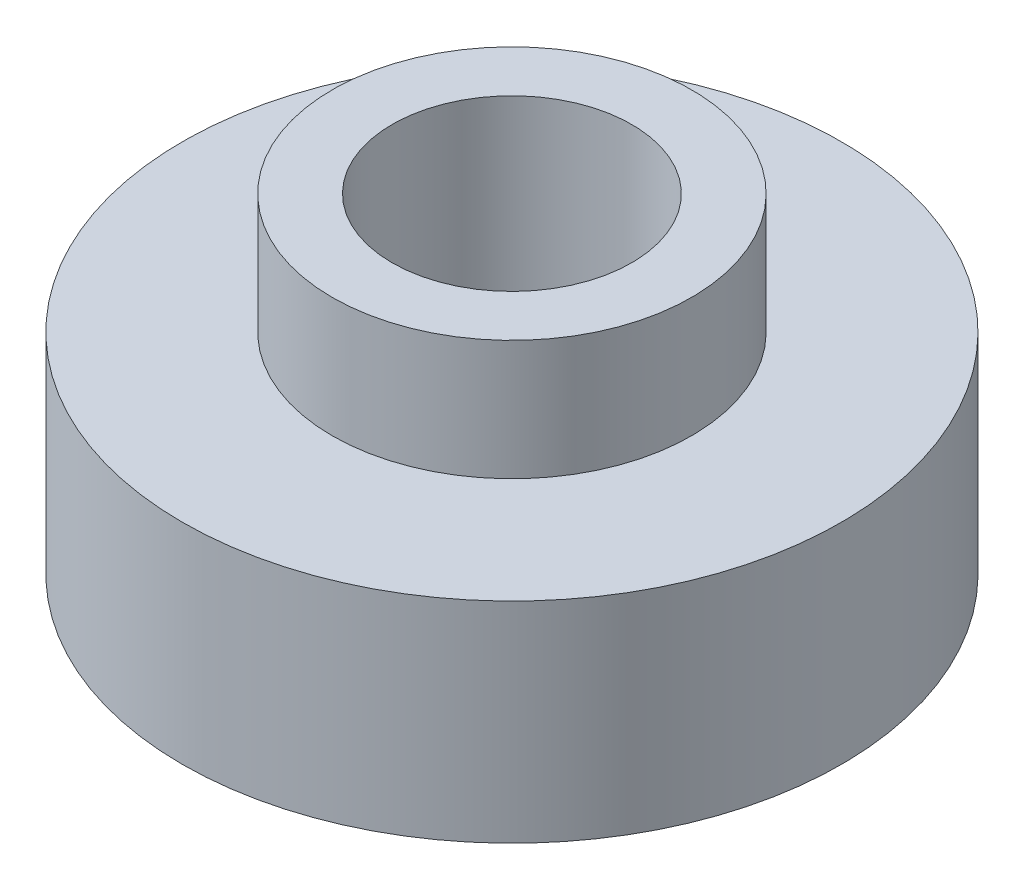
SolidWorks part; units mm, degrees
ref_plane "Front Plane" through (0, 0, 0) normal (0, 0, 1) x (1, 0, 0)
ref_plane "Top Plane" through (0, 0, 0) normal (0, 1, 0) x (1, 0, 0)
ref_plane "Right Plane" through (0, 0, 0) normal (1, 0, 0) x (0, 0, -1)
sketch "Sketch1" plane through (0, 0, 0) normal (0, 1, 0) x (1, 0, 0)
  circle A0 centre (0, 0) radius 11
extrude "Boss-Extrude1" add sketch "Sketch1" along normal blind 7
sketch "Sketch2" plane through (0, 7, 0) normal (0, 1, 0) x (1, 0, 0)
  circle A0 centre (0, 0) radius 6
extrude "Boss-Extrude3" add sketch "Sketch2" along normal blind 4
sketch "Sketch4" plane through (0, 11, 0) normal (0, 1, 0) x (1, 0, 0)
  circle A0 centre (0, 0) radius 4
extrude "Cut-Extrude1" cut sketch "Sketch4" against normal blind 11
